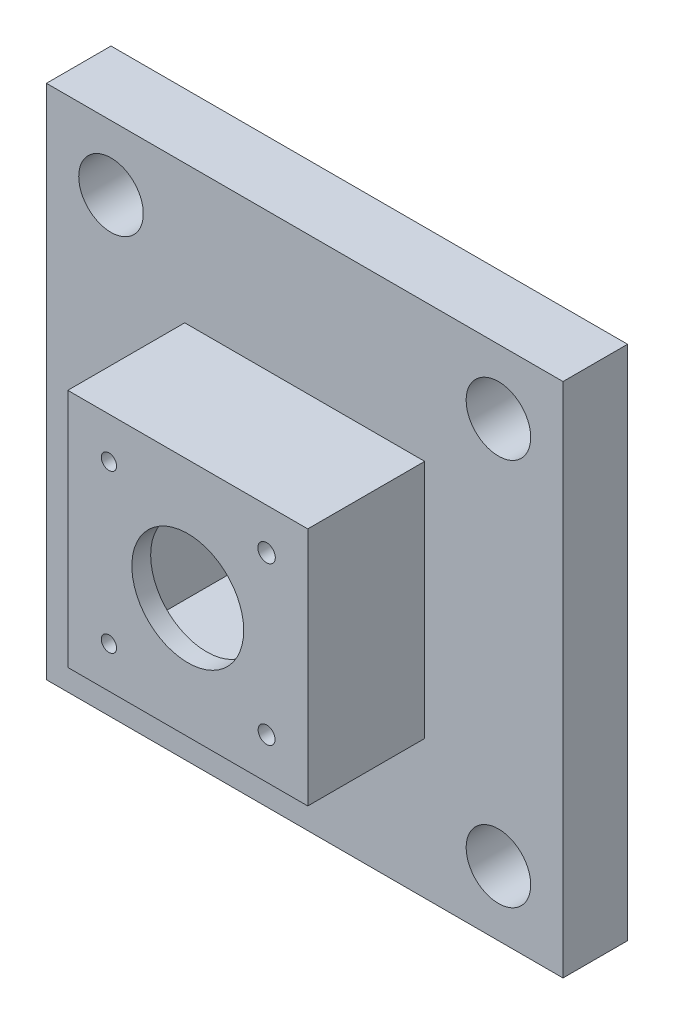
SolidWorks part; units mm, degrees
ref_plane "Front Plane" through (0, 0, 0) normal (0, 0, 1) x (1, 0, 0)
ref_plane "Top Plane" through (0, 0, 0) normal (0, 1, 0) x (1, 0, 0)
ref_plane "Right Plane" through (0, 0, 0) normal (1, 0, 0) x (0, 0, -1)
sketch "Sketch1" plane through (0, 0, 0) normal (0, 0, 1) x (1, 0, 0)
  line L1 (0, 0) -> (101.6, 0)
  line L2 (0, 0) -> (0, 101.6)
  line L3 (0, 101.6) -> (101.6, 101.6)
  line L4 (101.6, 0) -> (101.6, 101.6)
extrude "Boss-Extrude1" add sketch "Sketch1" along normal blind 12.7
sketch "Sketch4" plane through (0, 0, 12.7) normal (0, 0, 1) x (1, 0, 0)
  line L1 (27.2, 27.2) -> (74.4, 27.2)
  line L2 (27.2, 27.2) -> (27.2, 74.4)
  line L3 (27.2, 74.4) -> (74.4, 74.4)
  line L4 (74.4, 27.2) -> (74.4, 74.4)
extrude "Boss-Extrude3" add sketch "Sketch4" along normal blind 23
sketch "Sketch5" plane through (0, 0, 0) normal (0, 0, -1) x (-1, 0, 0)
  line L1 (-29.3, 29.3) -> (-71.6, 29.3)
  line L2 (-29.3, 29.3) -> (-29.3, 71.6)
  line L3 (-29.3, 71.6) -> (-71.6, 71.6)
  line L4 (-71.6, 29.3) -> (-71.6, 71.6)
extrude "Cut-Extrude1" cut sketch "Sketch5" against normal blind 32
sketch "Sketch6" plane through (0, 0, 35.7) normal (0, 0, 1) x (1, 0, 0)
  circle A0 centre (50.8, 50.8) radius 11
  circle A1 centre (35.3, 66.3) radius 1.5
  circle A2 centre (66.3, 66.3) radius 1.7152
  circle A3 centre (66.3, 35.3) radius 1.6615
  circle A4 centre (35.3, 35.3) radius 1.5
extrude "Cut-Extrude2" cut sketch "Sketch6" against normal blind 10
sketch "Sketch7" plane through (27.2, 0, 0) normal (-1, 0, 0) x (0, 0, 1)
  line L0 (12.7, 74.4) -> (12.7, 27.2) construction
  line L1 (12.7, 45.8) -> (18, 45.8)
  line L2 (12.7, 45.8) -> (12.7, 55.8)
  line L3 (12.7, 55.8) -> (18, 55.8)
  line L4 (18, 45.8) -> (18, 55.8)
extrude "Cut-Extrude3" cut sketch "Sketch7" against normal blind 5
sketch "Sketch8" plane through (0, 0, 12.7) normal (0, 0, 1) x (1, 0, 0)
  line L1 (27.2, 55.8) -> (21.9, 55.8)
  line L2 (27.2, 55.8) -> (27.2, 45.8)
  line L3 (27.2, 45.8) -> (21.9, 45.8)
  line L4 (21.9, 55.8) -> (21.9, 45.8)
extrude "Cut-Extrude5" cut sketch "Sketch8" against normal blind 12.7
sketch "Sketch9" plane through (0, 0, 0) normal (0, 0, -1) x (-1, 0, 0)
  circle A0 centre (-88.9, 88.9) radius 6.35
  circle A1 centre (-12.7, 88.9) radius 6.35
  circle A2 centre (-12.7, 12.7) radius 6.35
  circle A3 centre (-88.9, 12.7) radius 6.35
extrude "Cut-Extrude6" cut sketch "Sketch9" against normal blind 12.7
